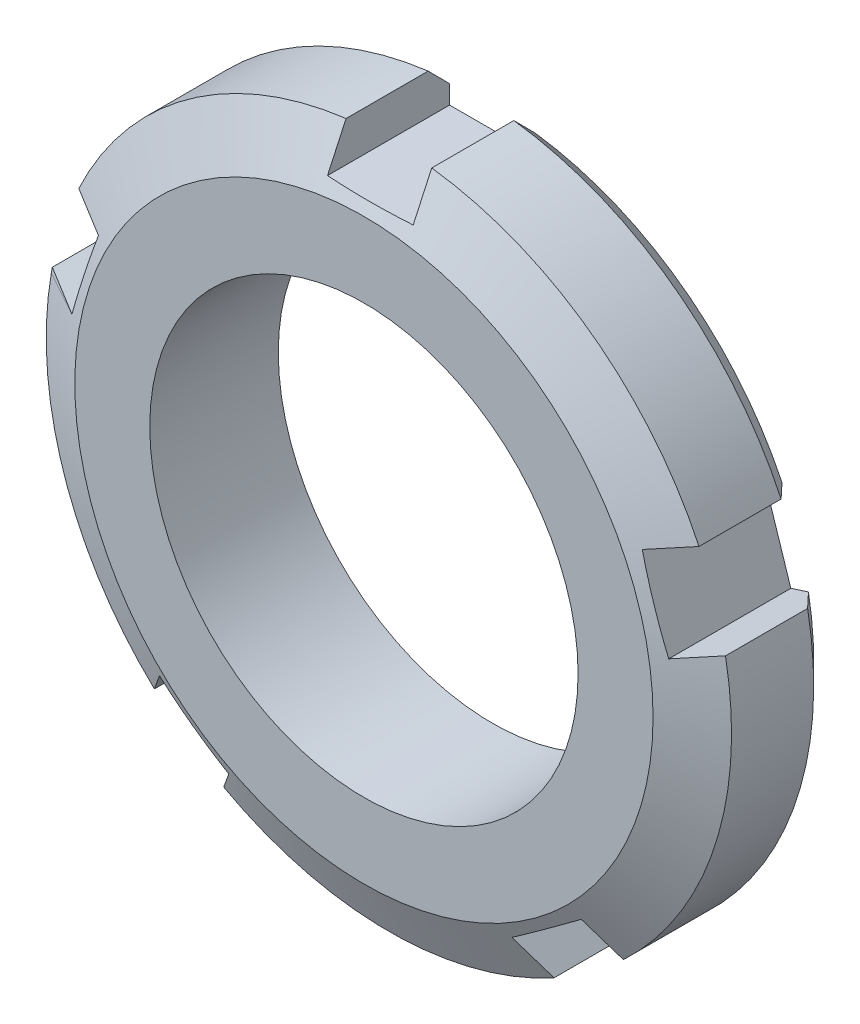
SolidWorks part; units mm, degrees
ref_plane "Front Plane" through (0, 0, 0) normal (0, 0, 1) x (1, 0, 0)
ref_plane "Top Plane" through (0, 0, 0) normal (0, 1, 0) x (1, 0, 0)
ref_plane "Right Plane" through (0, 0, 0) normal (1, 0, 0) x (0, 0, -1)
sketch "Sketch1" plane through (0, 0, 0) normal (1, 0, 0) x (0, 0, -1)
  line L0 (-16.3452, 0) -> (34.4162, 0) construction
  line L1 (0, 10) -> (6, 10)
  line L2 (6, 10) -> (6, 15)
  line L3 (6, 15) -> (5, 16)
  line L4 (5, 16) -> (1.1658, 16)
  line L5 (1.1658, 16) -> (0, 13.5)
  line L6 (0, 13.5) -> (0, 10)
  dimension "D1" = 20
  dimension "D2" = 32
  dimension "D3" = 6
  dimension "D4" = 45
  dimension "D5" = 25
  dimension "D6" = 2.5
  dimension "D7" = 1
revolve "Revolve1" add sketch "Sketch1" angle 360 about L0
sketch "Sketch2" plane through (0, 0, 0) normal (0, 0, 1) x (1, 0, 0)
  line L1 (-2, 16) -> (2, 16)
  line L2 (-2, 16) -> (-2, 14)
  line L3 (-2, 14) -> (2, 14)
  line L4 (2, 16) -> (2, 14)
  circle A0 centre (0, 0) radius 16 construction
  point P4 (0, 14)
  dimension "D1" = 4
  dimension "D2" = 2
extrude "Cut-Extrude1" cut sketch "Sketch2" against normal through all
pattern_circular "CirPattern1" count 5 over 360 about axis through (0, 0, 0) along (0, 0, 1) of "Cut-Extrude1"
equation "\"D1@Sketch1\"=\"d_int_ecrou_encouch_matrice\""
equation "\"D3@Sketch1\"=\"b_ecrou_encouch_matrice\""
equation "\"D1@Sketch2\"=\"s_ecrou_encouch_matrice\""
equation "\"D2@Sketch2\"=\"s_ecrou_encouch_matrice\"/2"
equation "\"d_ext_rouleau\"= 90"
equation "\"epaisseur_rouleau\"=80"
equation "\"alesage-rouleau\"= 52"
equation "\"jeu_dent_rouleau\"= 2"
equation "\"profondeur_dent_rouleau\"=4"
equation "\"n_dent_roueau\"= 15"
equation "\"d_ext_roulement_rouleau\"= 42"
equation "\"d_int_roulement_rouleau\"= 20"
equation "\"B_roulement_rouleau\"= 12"
equation "\"r_roulement_rouleau\"= 0.6"
equation "\"d_bille_roulement_rouleau\"= 8"
equation "\"F_anneau_alesage_rouleau\"=1.85"
equation "\"G_anneau_alesage_rouleau\"=47.5"
equation "\"K_anneau_alesage_rouleau\"=3.75"
equation "\"d_vis_flasque_rouleau\"=5"
equation "\"l-x_vis_flasque_rouleau\"=4"
equation "\"g_anneau_arbre_rouleau\"=19"
equation "\"f_anneau_arbre_rouleau\"=1.3"
equation "\"k_anneau_arbre_rouleau\"=1.5"
equation "\"h_matrice\"= 22"
equation "\"d_matrice\"= 220"
equation "\"d_granulat\"= 8"
equation "\"zone_vide_matrice\" = 48"
equation "\"d_alesage_matrice\"=20"
equation "\"a_clavette_alesage_matrice\"=6"
equation "\"entrax_vis_rouleau\"=65"
equation "\"B_roulement_matrice\"= 12"
equation "\"d_ext_roulement_matrice\"= 42"
equation "\"d_int_roulement_matrice\"= 20"
equation "\"r_roulement_matrice\"= 1"
equation "\"h_epaulement_arbre_matrice\" = 80"
equation "\"h_polie_matrice\" = 40"
equation "\"l_arbre_matrice\" = 300"
equation "\"d_int_ecrou_encouch_matrice\" = 20"
equation "\"d_ext_ecrou_encouch_matrice\" = 32"
equation "\"b_ecrou_encouch_matrice\" = 6"
equation "\"s_ecrou_encouch_matrice\" = 4"
equation "\"D2@Sketch1\"=\"d_ext_ecrou_encouch_matrice\""
equation "\"G_ecrou_encouch_matrice\" = 1"
equation "\"E_ecrou_encouch_matrice\" = 4"
